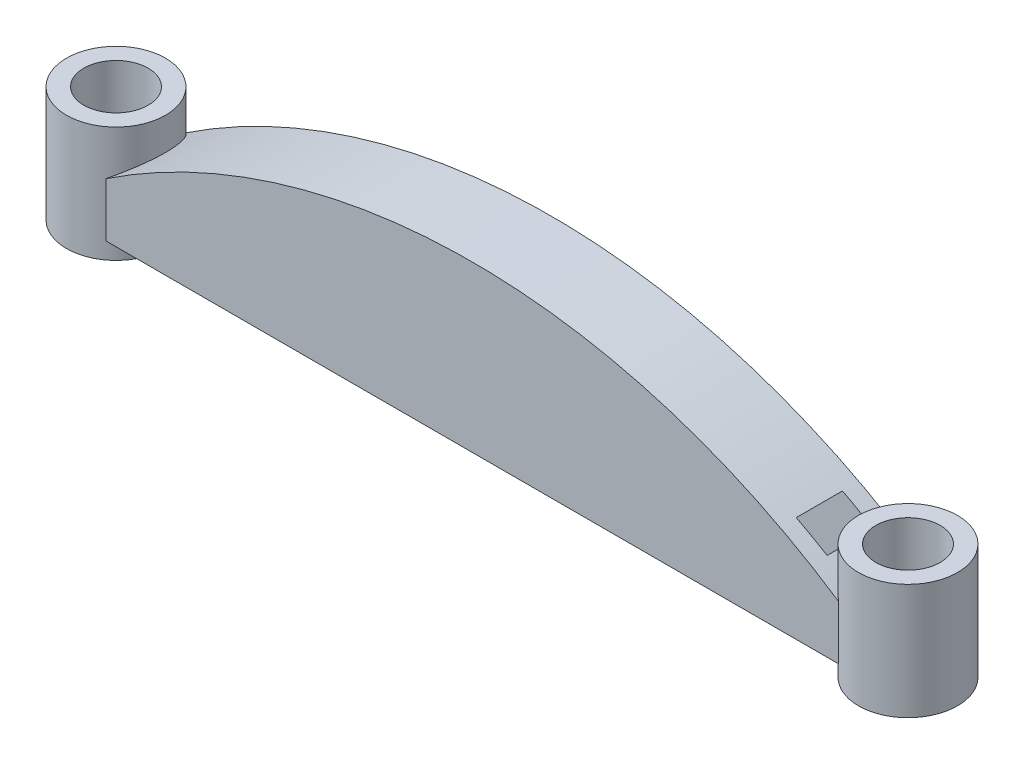
SolidWorks part; units mm, degrees
ref_plane "Спереди" through (0, 0, 0) normal (0, 0, 1) x (1, 0, 0)
ref_plane "Сверху" through (0, 0, 0) normal (0, 1, 0) x (1, 0, 0)
ref_plane "Справа" through (0, 0, 0) normal (1, 0, 0) x (0, 0, -1)
other "Configuration Table"
sketch "Эскиз2" plane through (0, 0, 0) normal (0, 0, 1) x (1, 0, 0)
  line L0 (0, 0) -> (0, 24.3243) construction
  line L1 (120, 0) -> (-120, 0)
  line L2 (-120, 0) -> (-120, 10)
  line L3 (120, 10) -> (120, 0)
  arc A0 (-120, 10) -> (120, 10) centre (0, -150) cw
  point P6 (0, 0)
  dimension "D1" = 200
  dimension "D3" = 50
  dimension "D2" = 240
extrude "Бобышка-Вытянуть2" add sketch "Эскиз2" along normal mid plane 24
sketch "Эскиз4" plane through (0, 0, 0) normal (0, -1, 0) x (1, 0, 0)
  line L0 (-120, 12) -> (-120, -12) construction
  line L1 (0, 45.1187) -> (0, -45.1187) construction
  circle A0 centre (-120, 0) radius 15
  circle A1 centre (120, 0) radius 15
  point P8 (0, 0)
  dimension "D1" = 30
extrude "Бобышка-Вытянуть3" add sketch "Эскиз4" against normal blind 30 and the other way blind 5
sketch "Эскиз5" plane through (0, 0, 0) normal (0, -1, 0) x (1, 0, 0)
  line L0 (204.4253, 0) -> (-204.4253, 0) construction
  line L1 (-102.5, 7) -> (-102.5, -7)
  line L2 (-102.5, -7) -> (-72.5, -7)
  line L3 (-72.5, -7) -> (-72.5, 7)
  line L4 (-72.5, 7) -> (-102.5, 7)
  circle A0 centre (-120, 0) radius 15 construction
  point P4 (0, 0)
  point P8 (-102.5, 0)
  dimension "D1" = 17.5
  dimension "D2" = 30
  dimension "D3" = 14
extrude "Вырез-Вытянуть2" cut sketch "Эскиз5" against normal offset from surface (31.0214 mm away) 5
pattern_linear "Линейный массив1" count 6 spacing 35 along (1, 0, 0) of "Вырез-Вытянуть2"
hole_wizard "Отверстие обработанное метчиком M221" positions "Эскиз8" profile "Эскиз9" tap size "M22" standard "ISO" end condition through all
sketch "Эскиз8" plane through (0, -5, 0) normal (0, -1, 0) x (-1, 0, 0)
  point P0 (-120, 0)
  point P3 (120, 0)
sketch "Эскиз9" plane through (120, -5, 0) normal (1, 0, 0) x (0, 0, -1)
  line L0 (0, 0) -> (0, 55)
  line L1 (0, 55) -> (9.75, 55)
  line L2 (9.75, 55) -> (9.75, 2.5)
  line L3 (9.75, 2.5) -> (12.25, 0)
  line L5 (12.25, 0) -> (0, 0)
  line L6 (-9.75, 2.5) -> (-12.25, 0) construction
  line L11 (0, -6.35) -> (0, 107.95) construction
  dimension "Диаметр проходного сверла" = 19.5
  dimension "Глубина проходного сверла" = 55
  dimension "Диаметр передней зенковки" = 24.5
  dimension "Угол передней зенковки" = 90
cosmetic thread "Отверстие резьбы1" parameters "D2"=22
cosmetic thread "Отверстие резьбы2" parameters "D2"=22
